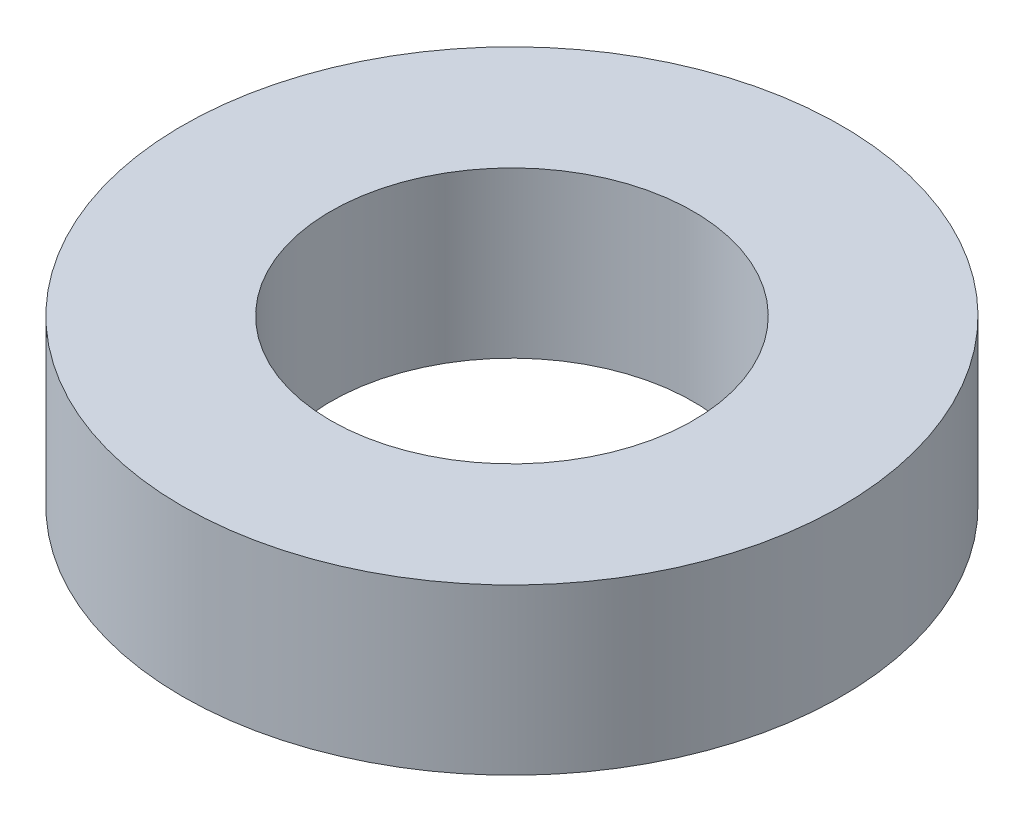
SolidWorks part; units mm, degrees
ref_plane "前视基准面" through (0, 0, 0) normal (0, 0, 1) x (1, 0, 0)
ref_plane "上视基准面" through (0, 0, 0) normal (0, 1, 0) x (1, 0, 0)
ref_plane "右视基准面" through (0, 0, 0) normal (1, 0, 0) x (0, 0, -1)
sketch "草图1" plane through (0, 0, 0) normal (0, 1, 0) x (1, 0, 0)
  circle A0 centre (0, 0) radius 1.65
  circle A1 centre (0, 0) radius 3
  dimension "D1" = 6
  dimension "D2" = 3.3
extrude "凸台-拉伸1" add sketch "草图1" along normal blind 1.5
